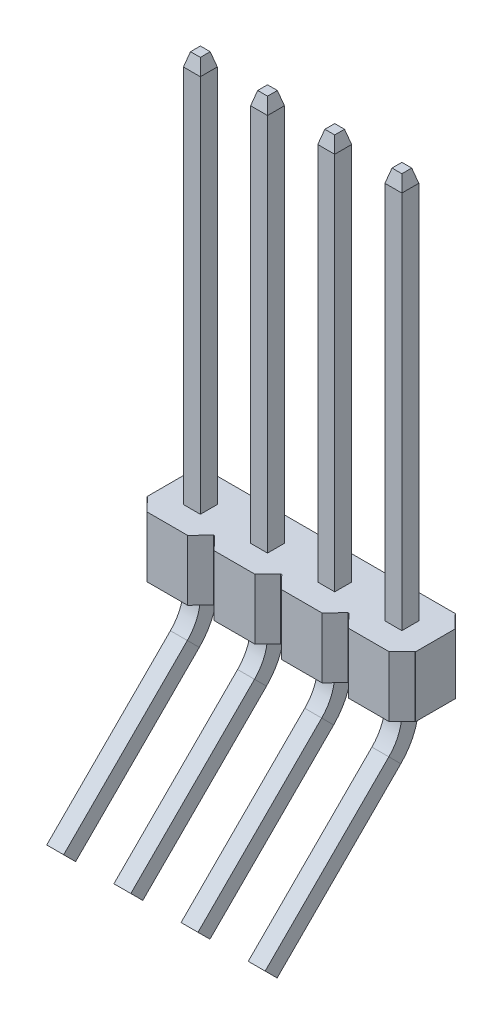
SolidWorks part; units mm, degrees
ref_plane "Front Plane" through (0, 0, 0) normal (0, 0, 1) x (1, 0, 0)
ref_plane "Top Plane" through (0, 0, 0) normal (0, 1, 0) x (1, 0, 0)
ref_plane "Right Plane" through (0, 0, 0) normal (1, 0, 0) x (0, 0, -1)
sketch "Sketch1" plane through (0, 0, 0) normal (0, 1, 0) x (1, 0, 0)
  line L14 (-0.77, 1.25) -> (0.77, 1.25)
  line L20 (-0.77, -1.25) -> (0.77, -1.25)
  line L22 (1.27, -0.75) -> (1.27, 0.75)
  line L23 (1.27, -1.25) -> (-1.27, 1.25) construction
  line L24 (0.77, -1.25) -> (1.25, -0.75)
  line L25 (1.25, -0.75) -> (1.27, -0.75)
  line L26 (0, 0) -> (0, -1.4708) construction
  line L27 (0, 0) -> (1.4893, 0) construction
  line L28 (0.77, 1.25) -> (1.25, 0.75)
  line L29 (1.25, 0.75) -> (1.27, 0.75)
  line L30 (-1.25, 0.75) -> (-1.27, 0.75)
  line L31 (-0.77, 1.25) -> (-1.25, 0.75)
  line L32 (-1.25, -0.75) -> (-1.27, -0.75)
  line L33 (-0.77, -1.25) -> (-1.25, -0.75)
  line L34 (-1.27, -0.75) -> (-1.27, 0.75)
  point P18 (0, 0)
  point P20 (0, 0)
  point P21 (0, 0)
  point P22 (0, 0)
  point P25 (0, 1.25)
  point P29 (0, 0)
  point P38 (1.27, 0)
  point P43 (0, -1.25)
  dimension "D11" = 1.25
  dimension "D12" = 1.27
  dimension "D13" = 0.5
  dimension "D14" = 0.02
  dimension "D15" = 0.5
extrude "Boss-Extrude1" add sketch "Sketch1" along normal blind 2.29
sketch "Sketch2" plane through (0, 0, 0) normal (1, 0, 0) x (0, 0, -1)
  line L0 (0, 17.12) -> (0, -0.4081)
  line L2 (-0.5858, -1.8224) -> (-5.2634, -6.5)
  line L3 (0.75, 0) -> (1.25, 0) construction
  arc A0 (0, -0.4081) -> (-0.5858, -1.8224) centre (-2, -0.4081) cw
  dimension "D4" = 2
  dimension "D1" = 23.62
  dimension "D2" = 135
  dimension "D3" = 6.5
ref_plane "Plane1" through (0, 17.12, 0) normal (0, 1, 0) x (1, 0, 0)
sketch "Sketch3" plane through (0, 17.12, 0) normal (0, 1, 0) x (1, 0, 0)
  line L1 (-0.32, 0.32) -> (0.32, 0.32)
  line L2 (-0.32, 0.32) -> (-0.32, -0.32)
  line L3 (-0.32, -0.32) -> (0.32, -0.32)
  line L4 (0.32, 0.32) -> (0.32, -0.32)
  line L5 (-0.32, 0.32) -> (0.32, -0.32) construction
  line L6 (-0.32, -0.32) -> (0.32, 0.32) construction
  point P0 (0, 0)
  dimension "D1" = 0.64
sweep "Sweep1" add profiles "Sketch3" path "Sketch2"
chamfer "Chamfer3" distance 0.5 angle 15 4 edges at (0, 17.12, 0.32) (-0.32, 17.12, 0) (0, 17.12, -0.32) (0.32, 17.12, 0)
pattern_linear "LPattern1" count 4 spacing 2.54 along (1, 0, 0) of "Boss-Extrude1", "Chamfer3", "Sweep1"
